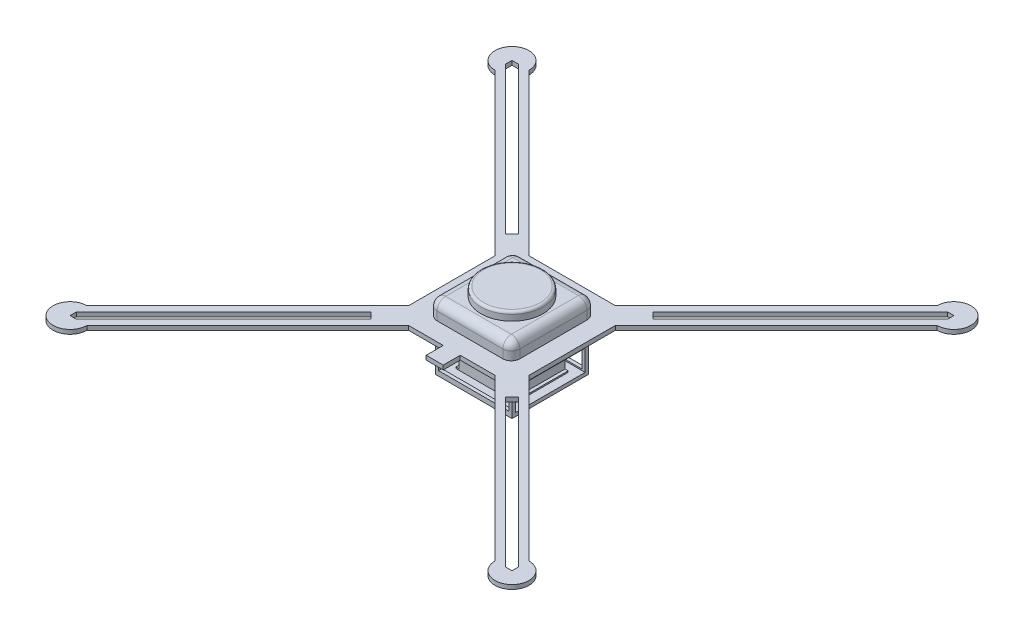
SolidWorks part; units mm, degrees
material "Thornel Mat VMA"
ref_plane "前视" through (0, 0, 0) normal (0, 0, 1) x (1, 0, 0)
ref_plane "上视" through (0, 0, 0) normal (0, 1, 0) x (1, 0, 0)
ref_plane "右视" through (0, 0, 0) normal (1, 0, 0) x (0, 0, -1)
sketch "草图1" plane through (0, 0, 0) normal (0, 1, 0) x (1, 0, 0)
  line L0 (0, 0) -> (260, 0)
  line L1 (260, 0) -> (260, 260)
  line L2 (260, 260) -> (0, 260)
  line L3 (0, 260) -> (0, 0)
  line L4 (0, 70.9035) -> (70.9035, 70.9035)
  line L5 (70.9035, 70.9035) -> (70.9035, 0)
  line L6 (63.5466, 70.9035) -> (252.6432, 260)
  line L7 (70.9035, 63.5466) -> (260, 252.6432)
  line L8 (50.8967, 70.9035) -> (239.9932, 260)
  line L9 (70.9035, 50.8967) -> (260, 239.9932)
  line L10 (72.9627, 92.9694) -> (92.9694, 72.9627)
  circle A0 centre (260, 260) radius 20.0068
extrude "凸台-拉伸1" add sketch "草图1" along normal blind 5 contours L5 L4 L3 L0 | L10 L8 L4 L6 | L10 L6 L4 L5 L7 | L10 L7 L5 L9 | A0 L8 L10 L6 | A0 L7 L10 L9 | L1 A0 L2 | L2 A0 L6 | L7 A0 L1
mirror "镜向1" about plane through (0, 5, 0) normal (1, 0, 0) of "凸台-拉伸1"
mirror "镜向3" about plane through (0, 5, 0) normal (0, 0, -1) of bodies 102
sketch "草图2" plane through (0, 0, 0) normal (0, -1, 0) x (1, 0, 0)
  line L1 (-45, -45) -> (45, -45)
  line L2 (-45, -45) -> (-45, 45)
  line L3 (-45, 45) -> (45, 45)
  line L4 (45, -45) -> (45, 45)
  line L5 (-45, -45) -> (45, 45) construction
  line L6 (-45, 45) -> (45, -45) construction
  point P0 (0, 0)
extrude "凸台-拉伸2" add sketch "草图2" along normal blind 25
sketch "草图3" plane through (0, 0, 45) normal (0, 0, 1) x (1, 0, 0)
  line L1 (-41.3339, -4.7178) -> (41.3339, -4.7178)
  line L2 (-41.3339, -4.7178) -> (-41.3339, -19.776)
  line L3 (-41.3339, -19.776) -> (41.3339, -19.776)
  line L4 (41.3339, -4.7178) -> (41.3339, -19.776)
  line L5 (-41.3339, -4.7178) -> (41.3339, -19.776) construction
  line L6 (-41.3339, -19.776) -> (41.3339, -4.7178) construction
  point P0 (0, -12.2469)
extrude "切除-拉伸1" cut sketch "草图3" against normal blind 90
sketch "草图4" plane through (45, 0, 0) normal (1, 0, 0) x (0, 0, -1)
  line L1 (-41.0428, -3.7748) -> (41.0428, -3.7748)
  line L2 (-41.0428, -3.7748) -> (-41.0428, -20.7699)
  line L3 (-41.0428, -20.7699) -> (41.0428, -20.7699)
  line L4 (41.0428, -3.7748) -> (41.0428, -20.7699)
  line L5 (-41.0428, -3.7748) -> (41.0428, -20.7699) construction
  line L6 (-41.0428, -20.7699) -> (41.0428, -3.7748) construction
  point P0 (0, -12.2724)
extrude "切除-拉伸2" cut sketch "草图4" against normal blind 90
sketch "草图5" plane through (0, 5, 0) normal (0, 1, 0) x (1, 0, 0)
  line L1 (-48.6824, 49.4718) -> (48.6824, 49.4718)
  line L2 (-48.6824, 49.4718) -> (-48.6824, -49.4718)
  line L3 (-48.6824, -49.4718) -> (48.6824, -49.4718)
  line L4 (48.6824, 49.4718) -> (48.6824, -49.4718)
  line L5 (-48.6824, 49.4718) -> (48.6824, -49.4718) construction
  line L6 (-48.6824, -49.4718) -> (48.6824, 49.4718) construction
  point P0 (0, 0)
extrude "凸台-拉伸3" add sketch "草图5" along normal blind 20
fillet "圆角1" radius 10 8 edges at (-48.6824, 15, -49.4718) (48.6824, 15, -49.4718) (48.6824, 15, 49.4718) (48.6824, 25, 0) (0, 25, -49.4718) (-48.6824, 15, 49.4718) (0, 25, 49.4718) (-48.6824, 25, 0)
sketch "草图6" plane through (0, -25, 0) normal (0, -1, 0) x (1, 0, 0)
  line L1 (-45, 45) -> (45, 45)
  line L2 (-45, 45) -> (-45, -45)
  line L3 (-45, -45) -> (45, -45)
  line L4 (45, 45) -> (45, -45)
extrude "凸台-拉伸4" add sketch "草图6" along normal blind 30
sketch "草图7" plane through (0, 0, 45) normal (0, 0, 1) x (1, 0, 0)
  line L0 (-41.3339, -25.4149) -> (41.3339, -25.4149)
  line L1 (41.3339, -25.4149) -> (41.3339, -49.3476)
  line L2 (41.3339, -49.3476) -> (31.3339, -49.3476)
  line L3 (-41.3339, -25.4149) -> (-41.3339, -49.3476)
  line L4 (-41.3339, -49.3476) -> (-31.3339, -49.3476)
  line L5 (-31.3339, -49.3476) -> (-31.3339, -36.2232)
  line L6 (-31.3339, -36.2232) -> (31.3339, -36.2232)
  line L7 (31.3339, -36.2232) -> (31.3339, -49.3476)
extrude "切除-拉伸3" cut sketch "草图7" against normal blind 90
sketch "草图8" plane through (0, 0, 45) normal (0, 0, 1) x (1, 0, 0)
  line L1 (-31.3339, -36.2232) -> (31.3339, -36.2232)
  line L2 (-31.3339, -36.2232) -> (-31.3339, -49.3476)
  line L3 (-31.3339, -49.3476) -> (31.3339, -49.3476)
  line L4 (31.3339, -36.2232) -> (31.3339, -49.3476)
extrude "切除-拉伸4" cut sketch "草图8" against normal blind 10
sketch "草图9" plane through (45, 0, 0) normal (1, 0, 0) x (0, 0, -1)
  line L0 (-41.0428, -26.2736) -> (-41.0428, -50.9435)
  line L1 (-41.0428, -26.2736) -> (41.0428, -26.2736)
  line L2 (41.0428, -26.2736) -> (41.0428, -50.9435)
  line L3 (41.0428, -50.9435) -> (31.0428, -50.9435)
  line L4 (-41.0428, -50.9435) -> (-31.0428, -50.9435)
  line L5 (-31.0428, -50.9435) -> (-31.0428, -29.3173)
  line L6 (-31.0428, -29.3173) -> (31.0428, -29.3173)
  line L7 (31.0428, -29.3173) -> (31.0428, -50.9435)
extrude "切除-拉伸5" cut sketch "草图9" against normal blind 90
sketch "草图10" plane through (45, 0, 0) normal (1, 0, 0) x (0, 0, -1)
  line L1 (-31.0428, -29.3173) -> (31.0428, -29.3173)
  line L2 (-31.0428, -29.3173) -> (-31.0428, -50.9435)
  line L3 (-31.0428, -50.9435) -> (31.0428, -50.9435)
  line L4 (31.0428, -29.3173) -> (31.0428, -50.9435)
extrude "切除-拉伸6" cut sketch "草图10" against normal blind 10
sketch "草图11" plane through (0, 0, -45) normal (0, 0, -1) x (-1, 0, 0)
  line L1 (-31.3339, -36.2232) -> (31.3339, -36.2232)
  line L2 (-31.3339, -36.2232) -> (-31.3339, -49.3476)
  line L3 (-31.3339, -49.3476) -> (31.3339, -49.3476)
  line L4 (31.3339, -36.2232) -> (31.3339, -49.3476)
extrude "切除-拉伸7" cut sketch "草图11" against normal blind 10
sketch "草图12" plane through (-45, 0, 0) normal (-1, 0, 0) x (0, 0, 1)
  line L1 (-31.0428, -29.3173) -> (31.0428, -29.3173)
  line L2 (-31.0428, -29.3173) -> (-31.0428, -50.9435)
  line L3 (-31.0428, -50.9435) -> (31.0428, -50.9435)
  line L4 (31.0428, -29.3173) -> (31.0428, -50.9435)
extrude "切除-拉伸8" cut sketch "草图12" against normal blind 10
sketch "草图13" plane through (0, 0, 70.9035) normal (0, 0, 1) x (1, 0, 0)
  line L0 (0, 0) -> (-10, 0)
  line L1 (-50.8967, 0) -> (50.8967, 0) construction
  line L2 (0, 0) -> (10, 0)
  line L3 (45, 0) -> (-45, 0) construction
  line L4 (10, 0) -> (10, 5)
  line L5 (-38.6824, 5) -> (38.6824, 5) construction
  line L6 (10, 5) -> (-10, 5)
  line L7 (-10, 5) -> (-10, 0)
extrude "凸台-拉伸5" add sketch "草图13" along normal blind 20
sketch "草图14" plane through (0, 25, 0) normal (0, 1, 0) x (1, 0, 0)
  circle A0 centre (0, 0) radius 36.4819
extrude "凸台-拉伸6" add sketch "草图14" along normal blind 10
fillet "圆角2" radius 3 1 edges at (0, 35, 36.4819)
